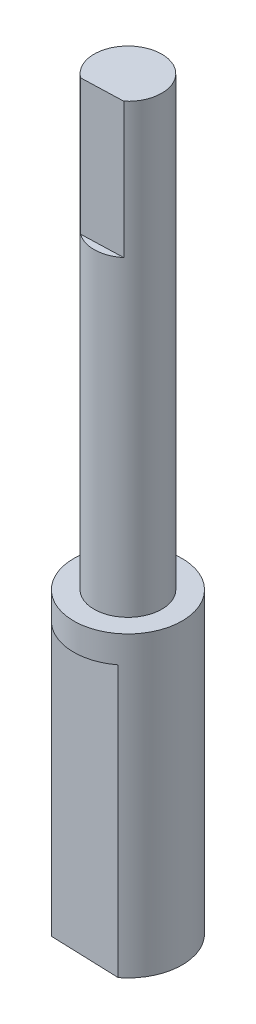
SolidWorks part; units mm, degrees
ref_plane "Front Plane" through (0, 0, 0) normal (0, 0, 1) x (1, 0, 0)
ref_plane "Top Plane" through (0, 0, 0) normal (0, 1, 0) x (1, 0, 0)
ref_plane "Right Plane" through (0, 0, 0) normal (1, 0, 0) x (0, 0, -1)
sketch "Sketch1" plane through (0, 0, 0) normal (0, 1, 0) x (1, 0, 0)
  circle A0 centre (0, 0) radius 4
extrude "Boss-Extrude1" add sketch "Sketch1" along normal blind 55
sketch "Sketch2" plane through (0, 0, 0) normal (0, -1, 0) x (1, 0, 0)
  line L0 (-2.6613, 2.9862) -> (2.4441, 3.1664)
  arc A0 (2.4441, 3.1664) -> (-2.6613, 2.9862) centre (0, 0) ccw
extrude "Cut-Extrude1" cut sketch "Sketch2" against normal blind 20
sketch "Sketch3" plane through (0, 55, 0) normal (0, 1, 0) x (1, 0, 0)
  circle A0 centre (0, 0) radius 2.5
  circle A1 centre (0, 0) radius 4
extrude "Cut-Extrude2" cut sketch "Sketch3" against normal blind 33
sketch "Sketch6" plane through (0, 55, 0) normal (0, 1, 0) x (1, 0, 0)
  line L0 (-1.4793, -2.0154) -> (1.607, -1.9151)
  arc A0 (-1.4793, -2.0154) -> (1.607, -1.9151) centre (0, 0) ccw
extrude "Cut-Extrude3" cut sketch "Sketch6" against normal blind 10
